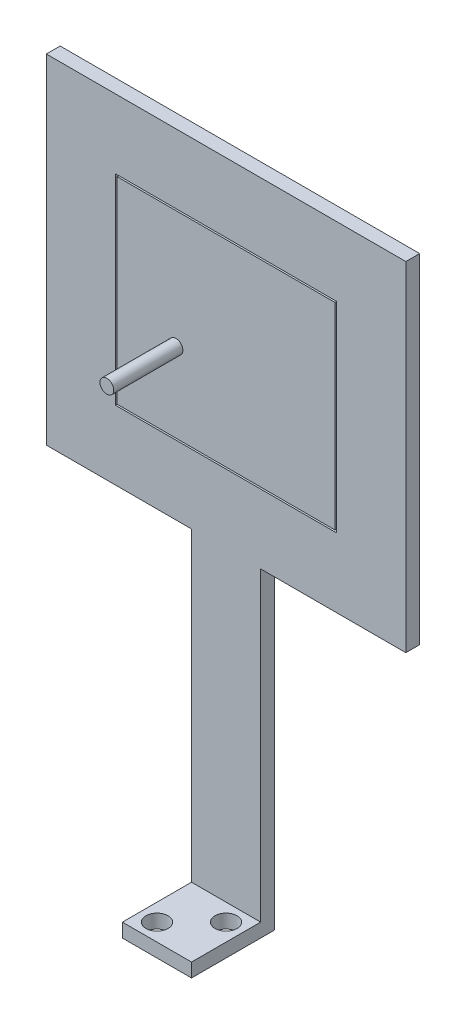
SolidWorks part; units mm, degrees
ref_plane "Front Plane" through (0, 0, 0) normal (0, 0, 1) x (1, 0, 0)
ref_plane "Top Plane" through (0, 0, 0) normal (0, 1, 0) x (1, 0, 0)
ref_plane "Right Plane" through (0, 0, 0) normal (1, 0, 0) x (0, 0, -1)
sketch "Sketch1" plane through (0, 0, 0) normal (0, 0, 1) x (1, 0, 0)
  line L0 (0, -17) -> (8.5, -17)
  line L1 (0, 0) -> (31.5, 0)
  line L2 (0, 0) -> (0, -28.5)
  line L3 (0, -28.5) -> (31.5, -28.5)
  line L4 (31.5, 0) -> (31.5, -28.5)
  circle A0 centre (8.5, -17) radius 1
  dimension "D5" = 2
  dimension "D1" = 28.5
  dimension "D2" = 31.5
  dimension "D3" = 11.5
  dimension "D4" = 8.5
extrude "Boss-Extrude2" add sketch "Sketch1" along normal blind 1.5
sketch "Sketch3" plane through (0, 0, 1.5) normal (0, 0, 1) x (1, 0, 0)
  line L0 (0, -17) -> (8.5, -17) construction
  line L1 (0, -17) -> (8.5, -17)
  line L4 (31.5, 0) -> (0, 0)
  line L5 (0, 0) -> (0, -28.5)
  line L6 (0, -28.5) -> (31.5, -28.5)
  line L7 (31.5, -28.5) -> (31.5, 0)
  line L8 (31.5, 0) -> (0, 0)
  line L9 (0, 0) -> (0, -28.5)
  line L10 (0, -28.5) -> (31.5, -28.5)
  line L11 (31.5, -28.5) -> (31.5, 0)
  line L12 (31.5, 0) -> (0, 0)
  line L13 (31.5, -28.5) -> (31.5, 0)
  line L14 (0, -28.5) -> (31.5, -28.5)
  line L15 (0, 0) -> (0, -28.5)
  line L16 (31.5, 0) -> (0, 0)
  line L17 (31.5, -28.5) -> (31.5, 0)
  line L18 (0, -28.5) -> (31.5, -28.5)
  line L19 (0, 0) -> (0, -28.5)
  circle A1 centre (8.5, -17) radius 1
  circle A2 centre (8.5, -17) radius 1
  dimension "D1" = 0
  dimension "D2" = 0
  dimension "D3" = 0
extrude "Boss-Extrude3" add sketch "Sketch3" along normal blind 10
sketch "Sketch4" plane through (0, 0, 1.5) normal (0, 0, 1) x (1, 0, 0)
  line L1 (0, 0) -> (31.5, 0)
  line L2 (0, 0) -> (0, -28.5)
  line L3 (0, -28.5) -> (31.5, -28.5)
  line L4 (31.5, 0) -> (31.5, -28.5)
  line L5 (-0.25, 0.25) -> (31.75, 0.25)
  line L6 (-0.25, 0.25) -> (-0.25, -28.75)
  line L7 (-0.25, -28.75) -> (31.75, -28.75)
  line L8 (31.75, 0.25) -> (31.75, -28.75)
  line L9 (-10.25, 10.25) -> (41.75, 10.25)
  line L10 (-10.25, 10.25) -> (-10.25, -38.75)
  line L11 (-10.25, -38.75) -> (41.75, -38.75)
  line L12 (41.75, 10.25) -> (41.75, -38.75)
  dimension "D1" = 0.25
  dimension "D2" = 0.25
  dimension "D3" = 0.25
  dimension "D4" = 0.25
  dimension "D5" = 10
  dimension "D6" = 10
  dimension "D7" = 10
  dimension "D8" = 10
extrude "Boss-Extrude4" add sketch "Sketch4" against normal blind 2 separate body contours L12 L9 L10 L11 L5 L8 L7 L6
sketch "Sketch6" plane through (0, -38.75, 0) normal (0, -1, 0) x (1, 0, 0)
  line L0 (0, 1.5) -> (31.5, 1.5) construction
  line L1 (10.75, 1.5) -> (20.75, 1.5)
  line L2 (10.75, 1.5) -> (10.75, -0.5)
  line L3 (10.75, -0.5) -> (20.75, -0.5)
  line L4 (20.75, 1.5) -> (20.75, -0.5)
  line L5 (-10.25, -0.5) -> (41.75, -0.5) construction
  line L6 (10.75, 1.5) -> (-10.25, 1.5) construction
  line L7 (20.75, 1.5) -> (41.75, 1.5) construction
  dimension "D1" = 10
extrude "Boss-Extrude5" add sketch "Sketch6" along normal blind 44.25
sketch "Sketch7" plane through (0, -83, 0) normal (0, -1, 0) x (1, 0, 0)
  line L0 (10.75, 11.5) -> (20.75, 1.5) construction
  line L1 (10.75, -0.5) -> (20.75, -0.5)
  line L2 (10.75, -0.5) -> (10.75, 11.5)
  line L3 (10.75, 11.5) -> (20.75, 11.5)
  line L4 (20.75, -0.5) -> (20.75, 11.5)
  circle A0 centre (13.2532, 8.9968) radius 1.6
  circle A1 centre (18.2468, 4.0032) radius 1.6
  point P5 (15.75, 6.5)
  point P8 (13.2532, 8.9968)
  point P9 (18.2468, 4.0032)
  dimension "D5" = 3.2
  dimension "D6" = 3.2
  dimension "D1" = 12
  dimension "D2" = 10
  dimension "D3" = 3.54
  dimension "D4" = 3.54
extrude "Boss-Extrude6" add sketch "Sketch7" along normal blind 2
